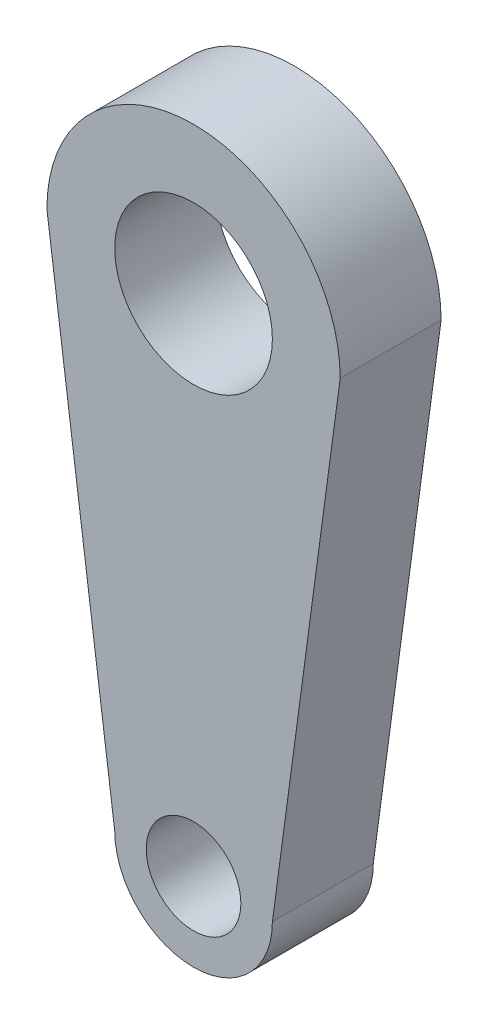
SolidWorks part; units mm, degrees
ref_plane "Alzado" through (0, 0, 0) normal (0, 0, 1) x (1, 0, 0)
ref_plane "Planta" through (0, 0, 0) normal (0, 1, 0) x (1, 0, 0)
ref_plane "Vista lateral" through (0, 0, 0) normal (1, 0, 0) x (0, 0, -1)
sketch "Croquis1" plane through (0, 0, 0) normal (0, 0, 1) x (1, 0, 0)
  line L2 (-4.65, 5.425) -> (-2.5, -10.575)
  line L3 (4.65, 5.425) -> (2.5, -10.575)
  circle A1 centre (0, 5.425) radius 2.5
  circle A3 centre (0, -10.575) radius 1.5
  arc A4 (-2.5, -10.575) -> (2.5, -10.575) centre (0, -10.575) ccw
  arc A5 (4.65, 5.425) -> (-4.65, 5.425) centre (0, 5.425) ccw
  dimension "D2" = 3
  dimension "D1" = 16
extrude "Saliente-Extruir1" add sketch "Croquis1" along normal blind 3.2
